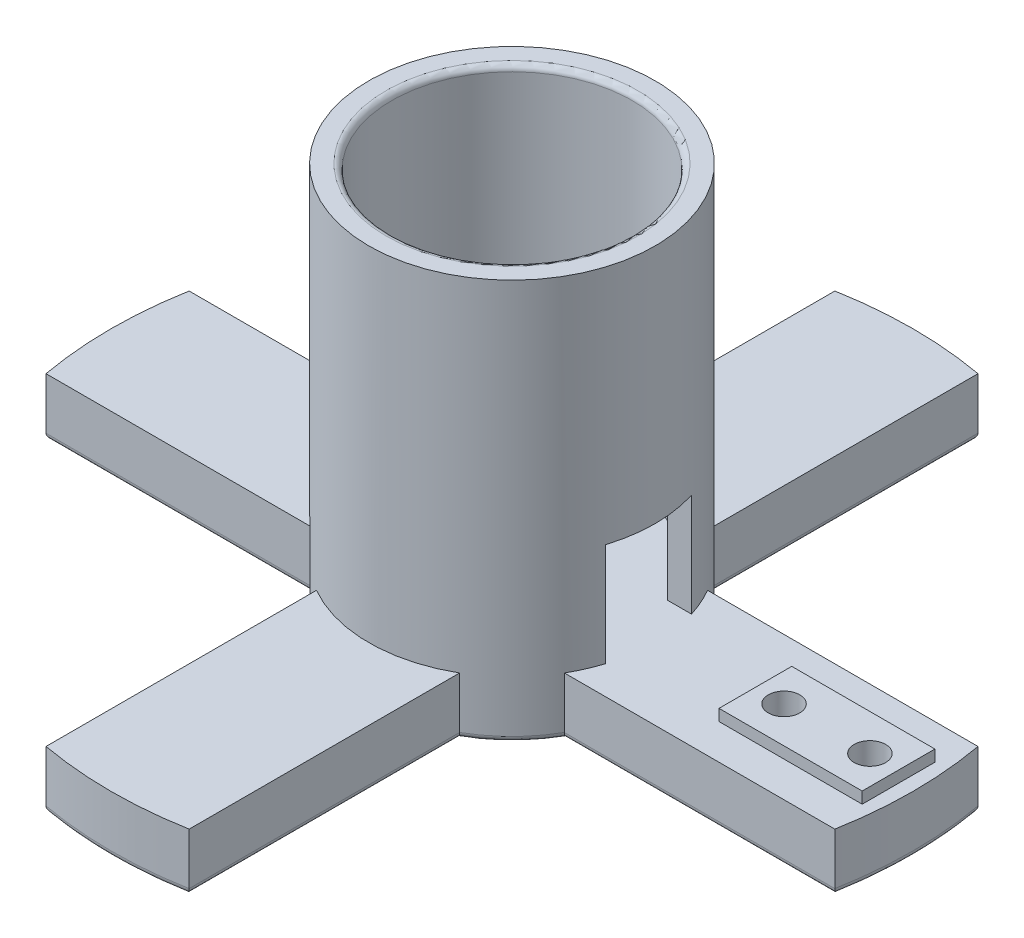
SolidWorks part; units mm, degrees
ref_plane "Front" through (0, 0, 0) normal (0, 0, 1) x (1, 0, 0)
ref_plane "Top" through (0, 0, 0) normal (0, 1, 0) x (1, 0, 0)
ref_plane "Right" through (0, 0, 0) normal (1, 0, 0) x (0, 0, -1)
sketch "Sketch1" plane through (0, 0, 0) normal (0, 1, 0) x (1, 0, 0)
  line L0 (-70, 0) -> (70, 0) construction
  line L1 (0, 70) -> (0, -70) construction
  line L2 (-68.8749, 12.5) -> (-21.6506, 12.5)
  line L3 (-68.8749, -12.5) -> (-21.6506, -12.5)
  line L4 (12.5, 68.8749) -> (12.5, 21.6506)
  line L5 (-12.5, 68.8749) -> (-12.5, 21.6506)
  line L6 (68.8749, -12.5) -> (21.6506, -12.5)
  line L7 (68.8749, 12.5) -> (21.6506, 12.5)
  line L8 (-12.5, -68.8749) -> (-12.5, -21.6506)
  line L9 (12.5, -68.8749) -> (12.5, -21.6506)
  arc A0 (-68.8749, 12.5) -> (-68.8749, -12.5) centre (0, 0) ccw
  arc A1 (-21.6506, -12.5) -> (-12.5, -21.6506) centre (0, 0) ccw
  arc A2 (-12.5, 21.6506) -> (-21.6506, 12.5) centre (0, 0) ccw
  arc A3 (21.6506, 12.5) -> (12.5, 21.6506) centre (0, 0) ccw
  arc A4 (12.5, -21.6506) -> (21.6506, -12.5) centre (0, 0) ccw
  arc A5 (12.5, 68.8749) -> (-12.5, 68.8749) centre (0, 0) ccw
  arc A6 (68.8749, -12.5) -> (68.8749, 12.5) centre (0, 0) ccw
  arc A7 (-12.5, -68.8749) -> (12.5, -68.8749) centre (0, 0) ccw
  point P27 (0, 0)
  dimension "D1" = 140
  dimension "D2" = 50
  dimension "D3" = 25
  dimension "D4" = 4
extrude "Boss-Extrude1" add sketch "Sketch1" along normal blind 10
sketch "Sketch2" plane through (0, 10, 0) normal (0, 1, 0) x (1, 0, 0)
  circle A0 centre (0, 0) radius 25
  circle A1 centre (0, 0) radius 21
  dimension "D1" = 42
extrude "Boss-Extrude2" add sketch "Sketch2" along normal blind 60
ref_plane "Plane1" through (25, 0, 0) normal (1, 0, 0) x (0, 0, -1)
sketch "Sketch3" plane through (25, 0, 0) normal (1, 0, 0) x (0, 0, -1)
  line L0 (0, 10) -> (0, 70) construction
  line L1 (12.5, 10) -> (-12.5, 10) construction
  line L2 (25, 70) -> (-25, 70) construction
  line L4 (-7.5, 28) -> (7.5, 28)
  line L5 (-7.5, 28) -> (-7.5, 10)
  line L6 (-7.5, 10) -> (7.5, 10)
  line L7 (7.5, 28) -> (7.5, 10)
  line L8 (-7.5, 28) -> (7.5, 10) construction
  line L9 (-7.5, 10) -> (7.5, 28) construction
  point P6 (0, 19)
  dimension "D1" = 15
  dimension "D2" = 18
extrude "Cut-Extrude1" cut sketch "Sketch3" against normal blind 10
sketch "Sketch4" plane through (0, 10, 0) normal (0, 1, 0) x (1, 0, 0)
  line L0 (70, 0) -> (25, 0) construction
  line L1 (25, -27.5) -> (25, 27.5) construction
  line L3 (42.5, 6.35) -> (67.5, 6.35)
  line L4 (42.5, 6.35) -> (42.5, -6.35)
  line L5 (42.5, -6.35) -> (67.5, -6.35)
  line L6 (67.5, 6.35) -> (67.5, -6.35)
  line L7 (42.5, 6.35) -> (67.5, -6.35) construction
  line L8 (42.5, -6.35) -> (67.5, 6.35) construction
  arc A0 (68.8749, -12.5) -> (68.8749, 12.5) centre (0, 0) ccw construction
  point P8 (55, 0)
  dimension "D1" = 12.7
  dimension "D2" = 25
  dimension "D3" = 55
extrude "Boss-Extrude3" add sketch "Sketch4" along normal blind 2
sketch "Sketch5" plane through (0, 12, 0) normal (0, 1, 0) x (1, 0, 0)
  line L0 (42.5, 0) -> (67.5, 0) construction
  line L1 (42.5, 6.35) -> (42.5, -6.35) construction
  line L2 (67.5, -6.35) -> (67.5, 6.35) construction
  line L3 (67.5, 6.35) -> (42.5, 6.35) construction
  line L4 (55, 6.35) -> (55, -6.35) construction
  line L5 (42.5, -6.35) -> (67.5, -6.35) construction
  circle A0 centre (47.5, 0) radius 2.75
  circle A1 centre (62.5, 0) radius 2.75
  dimension "D2" = 5.5
  dimension "D1" = 15
extrude "Cut-Extrude2" cut sketch "Sketch5" against normal through all
sketch "Sketch6" plane through (0, 0, 0) normal (0, -1, 0) x (1, 0, 0)
  circle A0 centre (47.5, 0) radius 5
  circle A1 centre (62.5, 0) radius 5
  dimension "D1" = 10
  dimension "D2" = 10
extrude "Cut-Extrude3" cut sketch "Sketch6" against normal blind 6
fillet "Fillet1" radius 1 19 edges at (-45.2628, 0, 12.5) (-17.6777, 0, 17.6777) (-12.5, 0, 45.2628) (0, 0, 70) (12.5, 0, 45.2628) (17.6777, 0, 17.6777) (45.2628, 0, 12.5) (70, 0, 0) (45.2628, 0, -12.5) (17.6777, 0, -17.6777) (12.5, 0, -45.2628) (0, 0, -70) (-12.5, 0, -45.2628) (-17.6777, 0, -17.6777) (-45.2628, 0, -12.5) (-70, 0, 0) (47.5, 0, -5) (62.5, 0, -5) (0, 70, 21)
